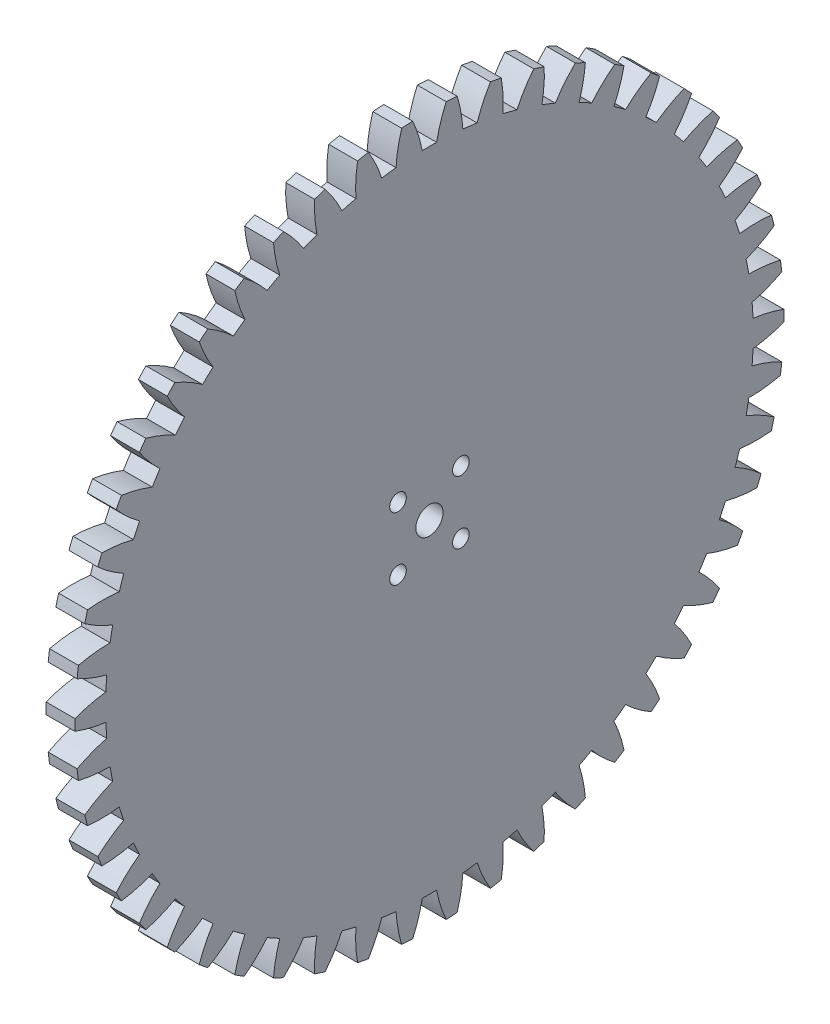
SolidWorks part; units mm, degrees
ref_plane "Plane1" through (0, 0, 0) normal (0, 0, 1) x (1, 0, 0)
ref_plane "Plane2" through (0, 0, 0) normal (0, 1, 0) x (1, 0, 0)
ref_plane "Plane3" through (0, 0, 0) normal (1, 0, 0) x (0, 0, -1)
sketch "HoldingSke" plane through (0, 0, 0) normal (0, 1, 0) x (1, 0, 0)
  line L0 (0, 0) -> (0.2143, -0.2553)
  line L1 (-15, 0) -> (100, 0) construction
  line L2 (0, 0) -> (-2.1039, 2.3779)
  line L3 (0, 0) -> (-11.863, 4.5341)
  line L4 (0, 0) -> (5.5511, 6.6156)
  line L5 (0, 0) -> (-46.8476, -17.4728)
  line L6 (0, 0) -> (-5.2639, -3.5516)
  line L7 (-2.1039, 2.3779) -> (8.6586, 51.2059)
  line L8 (-76.2, 54.61) -> (-75.2, 54.61)
  line L9 (-67.7845, 28.3722) -> (-49.3413, 33.142)
  line L10 (-76.2, 71.12) -> (104.1128, 71.12)
  line L11 (0, 0) -> (-6.35, 0)
  line L12 (-76.2, 101.6) -> (-76.093, 101.6)
  line L13 (24.9733, 27.94) -> (52.9518, 28.4284)
  line L14 (24.9733, 27.94) -> (24.9743, 27.94)
  line L15 (24.9733, 27.94) -> (100.4006, 29.5858)
  line L16 (-63.627, -3) -> (-12.827, -3)
  circle A0 centre (0, 0) radius 3
  circle A1 centre (0, 0) radius 37.5
  circle A2 centre (0, 0) radius 37.5
  circle A3 centre (0, 0) radius 3
  dimension "MHD" = 75
  dimension "Hub_dia" = 75
  dimension "Bore" = 6
  dimension "MBD" = 6
  dimension "Num_teeth" = 50
  dimension "Pitch" = 0.3333
  dimension "Overall_len" = 50
  dimension "Show_teeth" = 50
  dimension "Thickness" = 6.35
  dimension "OAL" = 50.0001
  dimension "T_dim" = 1
  dimension "Ap" = 14.5
  dimension "H" = 19.05
  dimension "Pitch_radius" = 180.3128
  dimension "Width" = 6.35
  dimension "Backlash" = 0.107
  dimension "Addendum_fac" = 1
  dimension "Dedendum_fac" = 1.25
  dimension "Clearance_fac" = 0.25
  dimension "Dedendum_add" = 0.001
  dimension "Module" = 3
sketch "BasProSke" plane through (0, 0, 0) normal (0, 1, 0) x (1, 0, 0)
  line L0 (-10, 0) -> (60, 0) construction
  line L1 (0, 0) -> (0, 78)
  line L2 (0, 0) -> (6.35, 0)
  line L3 (6.35, 0) -> (6.35, 78)
  line L4 (6.35, 78) -> (0, 78)
  dimension "Thickness" = 6.35
  dimension "Diameter" = 156
revolve "Base-Revolve" add sketch "BasProSke" angle 360 about L0
sketch "TooCutSke" plane through (0, 0, 0) normal (1, 0, 0) x (0, 0, -1)
  line L1 (0, 0) -> (0, 107) construction
  line L2 (0, 0) -> (-2.543, 74.9569) construction
  line L3 (0, 0) -> (-9.4146, 149.6414) construction
  line L4 (-2.543, 74.9569) -> (-4.7073, 74.8207) construction
  arc A0 (1.5844, 71.2314) -> (-1.5844, 71.2314) centre (0, 0) ccw
  arc A1 (3.6968, 77.9378) -> (-3.6968, 77.9378) centre (0, 0) ccw
  circle A2 centre (0, 0) radius 75 construction
  circle A3 centre (0, 0) radius 72.6111 construction
  arc A4 (-1.5844, 71.2314) -> (-3.6968, 77.9378) centre (-31.0576, 65.6338) ccw
  arc A5 (3.6968, 77.9378) -> (1.5844, 71.2314) centre (31.0576, 65.6338) ccw
  dimension "Root_dia" = 142.498
  dimension "Overcut_dia" = 156.0508
  dimension "Pitch_dia" = 150
  dimension "Base_dia" = 145.2221
  dimension "Flank_rad" = 30
  dimension "Half_ang" = 3.6
  dimension "Half_CT" = 2.1686
extrude "ToothCut" cut sketch "TooCutSke" along normal through all
fillet "Breaks" [suppressed] radius 0.06
fillet "RootFillets" [suppressed] radius 0.751
pattern_circular "TeethCuts" count 50 every 7.2 about axis through (-10, 0, 0) along (1, 0, 0) of "ToothCut", "RootFillets", "Breaks"
sketch "HubNeaOneSke" plane through (0, 0, 0) normal (-1, 0, 0) x (0, 0, 1)
  circle A0 centre (0, 0) radius 37.5
  dimension "Diameter" = 75
extrude "HubNearOne" [suppressed] add sketch "HubNeaOneSke" along normal blind 43.6501
sketch "HubNeaBotSke" plane through (0, 0, 0) normal (-1, 0, 0) x (0, 0, 1)
  circle A0 centre (0, 0) radius 37.5
  dimension "Diameter" = 75
extrude "HubNearBoth" [suppressed] add sketch "HubNeaBotSke" along normal blind 21.825
ref_plane "FarPln" through (6.35, 0, 0) normal (1, 0, 0) x (0, 0, -1)
sketch "HubFarSke" plane through (6.35, 0, 0) normal (1, 0, 0) x (0, 0, -1)
  circle A0 centre (0, 0) radius 37.5
  dimension "Diameter" = 75
extrude "HubFar" [suppressed] add sketch "HubFarSke" along normal blind 21.825
sketch "BorSke" plane through (0, 0, 0) normal (1, 0, 0) x (0, 0, -1)
  circle A0 centre (0, 0) radius 3
  dimension "Diameter" = 6
extrude "Bore" cut sketch "BorSke" along normal mid plane 100.0001
sketch "KeySke" plane through (0, 0, 0) normal (1, 0, 0) x (0, 0, -1)
  line L0 (-1, 0) -> (-1, 4)
  line L1 (-1, 4) -> (1, 4)
  line L2 (1, 4) -> (1, 0)
  line L3 (0, 0) -> (0, 34) construction
  line L4 (-1, 0) -> (1, 0)
  dimension "Offset" = 4
  dimension "Width" = 2
extrude "Keyway" [suppressed] cut sketch "KeySke" along normal mid plane 100.0001
pattern_circular "Keyway2" [suppressed] count 2 every 90 about axis through (-10, 0, 0) along (1, 0, 0)
sketch "Esquisse1" plane through (0, 0, 0) normal (-1, 0, 0) x (0, 0, 1)
  circle A0 centre (6.9148, 6.9148) radius 1.83
  dimension "D1" = 3.66
extrude "Enlèv. mat.-Extru.1" cut sketch "Esquisse1" against normal up to next
pattern_circular "Répétition circulaire1" count 4 every 90 about axis through (0, 0, 0) along (1, 0, 0) of "Enlèv. mat.-Extru.1"
equation "' \"Module@HoldingSke\" = 6.35"
equation "' \"Num_teeth@HoldingSke\" = 12"
equation "' \"Ap@HoldingSke\" =  20"
equation "' \"Ap@HoldingSke\" = 20"
equation "' \"Width@HoldingSke\" = 0.5 * 25.4"
equation "' \"Hub_dia@HoldingSke\"= 1 * 25.4"
equation "' \"Hub_dia@HoldingSke\" = 1 * 25.4"
equation "' \"Overall_len@HoldingSke\" = 1.0 * 25.4"
equation "' \"Bore@HoldingSke\" = 0.75 * 25.4"
equation "' \"T_dim@HoldingSke\" = 0.1 * 25.4"
equation "' \"Width@KeySke\" = 0.25 * 25.4"
equation "' \"Show_teeth@HoldingSke\" = 13"
equation "' \"Backlash@HoldingSke\" = 0.009 * 25.4"
equation "' \"Addendum_fac@HoldingSke\" = 1.0"
equation "' \"Dedendum_fac@HoldingSke\" = 1.25"
equation "' \"Dedendum_add@HoldingSke\" = 0.00005 * 25.4"
equation "' \"Clearance_fac@HoldingSke\" = 0.25"
equation "\"Pitch@HoldingSke\" = 1 / \"Module@HoldingSke\""
equation "\"Overcut_dia@TooCutSke\" = (\"Num_teeth@HoldingSke\" + 2 * \"Addendum_fac@HoldingSke\") / \"Pitch@HoldingSke\" + 0.002 * 25.4"
equation "\"Pitch_dia@TooCutSke\" = \"Num_teeth@HoldingSke\" / \"Pitch@HoldingSke\""
equation "\"Base_dia@TooCutSke\" = \"Num_teeth@HoldingSke\" / \"Pitch@HoldingSke\" * cos((\"Ap@HoldingSke\"  * 3.14159265 / 180))"
equation "\"Root_dia@TooCutSke\" = (\"Num_teeth@HoldingSke\" + 2) / \"Pitch@HoldingSke\" - 2 * (\"Addendum_fac@HoldingSke\" + \"Dedendum_fac@HoldingSke\") / \"Pitch@HoldingSke\" - \"Dedendum_add@HoldingSke\" * 2"
equation "\"Half_ang@TooCutSke\" = 180 / \"Num_teeth@HoldingSke\""
equation "\"Half_CT@TooCutSke\" = \"Num_teeth@HoldingSke\" / \"Pitch@HoldingSke\" * sin((3.14159265 / 2 / \"Num_teeth@HoldingSke\")) / 2 - 7 * \"Backlash@HoldingSke\" / 4"
equation "\"Flank_rad@TooCutSke\" = \"Num_teeth@HoldingSke\" / \"Pitch@HoldingSke\" / 5"
equation "\"Radius@RootFillets\" = \"Clearance_fac@HoldingSke\" / \"Pitch@HoldingSke\" + \"Dedendum_add@HoldingSke\""
equation "\"Break_rad@Breaks\" = 0.02 / \"Pitch@HoldingSke\""
equation "\"Thickness@HoldingSke\" = \"Width@HoldingSke\""
equation "\"OAL@HoldingSke\" = \"Thickness@HoldingSke\""
equation "\"MHD@HoldingSke\" = (\"Num_teeth@HoldingSke\" + 2) / \"Pitch@HoldingSke\" - 2 * (\"Addendum_fac@HoldingSke\" + \"Dedendum_fac@HoldingSke\")  / \"Pitch@HoldingSke\" - \"Dedendum_add@HoldingSke\" * 2"
equation "\"MBD@HoldingSke\" = (\"Num_teeth@HoldingSke\" + 2) / \"Pitch@HoldingSke\" - 2 * (\"Addendum_fac@HoldingSke\" + \"Dedendum_fac@HoldingSke\")  / \"Pitch@HoldingSke\" - \"Dedendum_add@HoldingSke\" * 2 - 0.002 * 25.4"
equation "\"MHD@HoldingSke\" = ((sgn( \"MHD@HoldingSke\" - \"Hub_dia@HoldingSke\" )-1)*( \"MHD@HoldingSke\" - \"Hub_dia@HoldingSke\" ))/-2+ \"Hub_dia@HoldingSke\""
equation "\"MBD@HoldingSke\" = ((sgn( \"MBD@HoldingSke\" - \"Bore@HoldingSke\" )-1)*( \"MBD@HoldingSke\" - \"Bore@HoldingSke\" ))/-2+ \"Bore@HoldingSke\""
equation "\"OAL@HoldingSke\" = ((sgn( \"OAL@HoldingSke\" - \"Overall_len@HoldingSke\" )+1)*( \"OAL@HoldingSke\" - \"Overall_len@HoldingSke\" ))/2 + \"Overall_len@HoldingSke\" + 0.000002 * 25.4"
equation "\"Num_teeth@TeethCuts\" = int( \"Show_teeth@HoldingSke\" ) + 1"
equation "\"Num_teeth@TeethCuts\" = ((sgn( \"Num_teeth@TeethCuts\" - \"Num_teeth@HoldingSke\" )-1)*( \"Num_teeth@TeethCuts\" - \"Num_teeth@HoldingSke\" ))/-2+ \"Num_teeth@HoldingSke\""
equation "\"Num_teeth@TeethCuts\" = ((sgn( \"Num_teeth@TeethCuts\" - 2.0)+1)*( \"Num_teeth@TeethCuts\" - 2.0))/2 +2.0"
equation "\"Angle@TeethCuts\" = 360.0 / \"Num_teeth@HoldingSke\""
equation "\"Diameter@BasProSke\" = (\"Num_teeth@HoldingSke\" + 2 * \"Addendum_fac@HoldingSke\") / \"Pitch@HoldingSke\""
equation "\"Thickness@BasProSke\"  = \"Thickness@HoldingSke\""
equation "' \"Fillet_rad@BasProSke\" =  \"Thickness@HoldingSke\" * 0.05"
equation "' \"Fillet_rad@BasProSke\" = \"Thickness@HoldingSke\" * 0.05"
equation "\"MHD@HoldingSke\" = ((sgn( \"MHD@HoldingSke\" - \"Root_dia@TooCutSke\" )-1)*( \"MHD@HoldingSke\" - \"Root_dia@TooCutSke\" ))/-2+ \"Root_dia@TooCutSke\""
equation "\"Diameter@HubNeaOneSke\" = \"MHD@HoldingSke\""
equation "\"Length@HubNearOne\" = \"OAL@HoldingSke\" - \"Thickness@BasProSke\""
equation "\"Diameter@HubNeaBotSke\" = \"MHD@HoldingSke\""
equation "\"Length@HubNearBoth\" = ( \"OAL@HoldingSke\" - \"Thickness@BasProSke\" ) / 2.0"
equation "\"Thickness@FarPln\" = \"Thickness@BasProSke\""
equation "\"Diameter@HubFarSke\" = \"MHD@HoldingSke\""
equation "\"Length@HubFar\" = ( \"OAL@HoldingSke\" - \"Thickness@BasProSke\" ) / 2.0"
equation "\"Diameter@BorSke\" = \"MBD@HoldingSke\""
equation "\"D1@Bore\" = \"OAL@HoldingSke\" * 2.0"
equation "\"D1@Keyway\" = \"OAL@HoldingSke\" * 2.0"
equation "\"Offset@KeySke\" = \"T_dim@HoldingSke\" + \"MBD@HoldingSke\" / 2.0"
